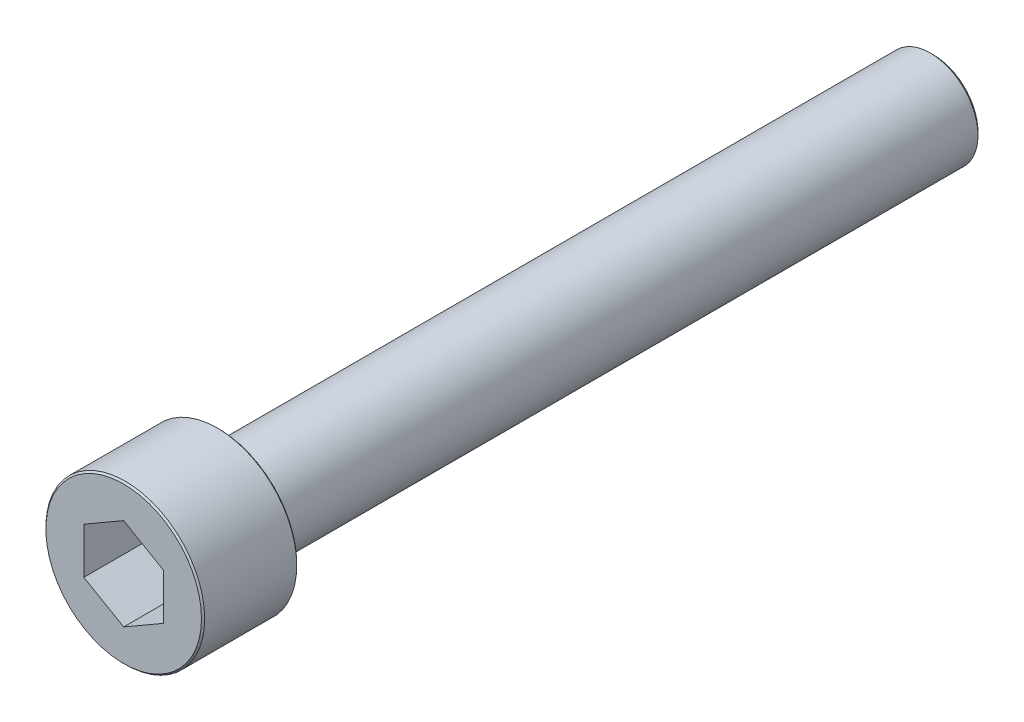
SolidWorks part; units mm, degrees
ref_plane "前视基准面" through (0, 0, 0) normal (0, 0, 1) x (1, 0, 0)
ref_plane "上视基准面" through (0, 0, 0) normal (0, 1, 0) x (1, 0, 0)
ref_plane "右视基准面" through (0, 0, 0) normal (1, 0, 0) x (0, 0, -1)
other "Configuration Table"
sketch "草图1" plane through (0, 0, 0) normal (0, 1, 0) x (1, 0, 0)
  line L0 (5, -45) -> (0, -45)
  line L1 (0, -45) -> (0, -51)
  line L2 (0, -51) -> (5, -51)
  line L3 (5, -51) -> (5, -45)
  line L4 (0, -45) -> (0, -51) construction
revolve "旋转1" add sketch "草图1" angle 360 about L4
sketch "草图2" plane through (0, 0, 45) normal (0, 0, -1) x (-1, 0, 0)
  circle A0 centre (0, 0) radius 3
extrude "凸台-拉伸1" add sketch "草图2" along normal blind 45
sketch "草图3" plane through (0, 0, 51) normal (0, 0, 1) x (1, 0, 0)
  line L0 (-2.51, -1.4491) -> (0, -2.8983)
  line L1 (0, -2.8983) -> (2.51, -1.4491)
  line L2 (2.51, -1.4491) -> (2.51, 1.4491)
  line L3 (2.51, 1.4491) -> (0, 2.8983)
  line L4 (0, 2.8983) -> (-2.51, 1.4491)
  line L5 (-2.51, 1.4491) -> (-2.51, -1.4491)
extrude "切除-拉伸1" cut sketch "草图3" against normal blind 4.5
chamfer "倒角1" distance 0.1 angle 45 2 edges at (5, 0, 45) (5, 0, 51)
chamfer "倒角2" distance 0.2001 angle 45.001 1 edges at (-3, 0, 0)
